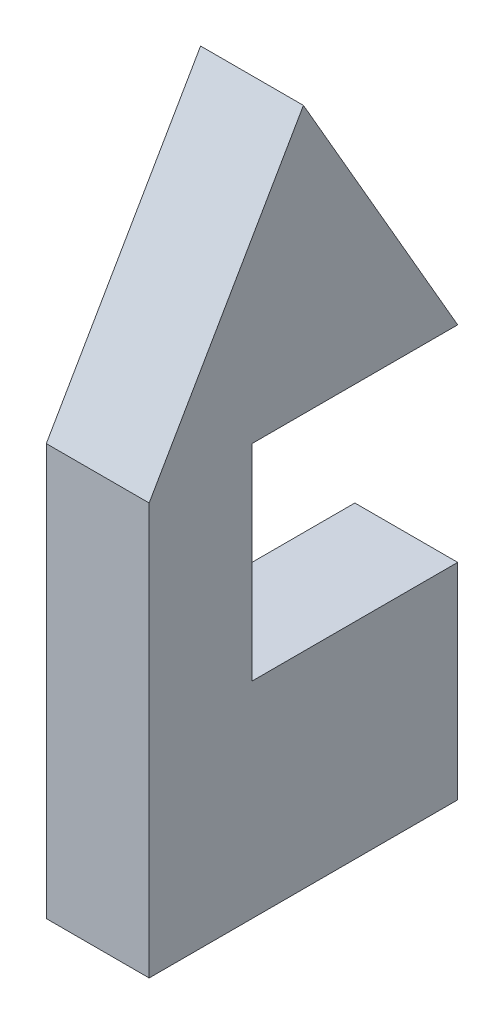
SolidWorks part; units mm, degrees
ref_plane "前视基准面" through (0, 0, 0) normal (0, 0, 1) x (1, 0, 0)
ref_plane "上视基准面" through (0, 0, 0) normal (0, 1, 0) x (1, 0, 0)
ref_plane "右视基准面" through (0, 0, 0) normal (1, 0, 0) x (0, 0, -1)
sketch "草图2" plane through (0, 0, 0) normal (1, 0, 0) x (0, 0, -1)
  line L1 (-2.6044, 1.2724) -> (-0.6044, 1.2724)
  line L2 (-3.6044, 1.2724) -> (-3.6044, -0.7276)
  line L3 (-3.6044, -0.7276) -> (-0.6044, -0.7276)
  line L4 (-0.6044, 1.2724) -> (-0.6044, -0.7276)
  line L8 (-3.6044, 3.2724) -> (-3.6044, 1.2724)
  line L10 (-2.6044, 3.2724) -> (-2.6044, 1.2724)
  line L13 (-0.6044, 3.2724) -> (-2.1044, 5.8705)
  line L14 (-2.1044, 5.8705) -> (-3.6044, 3.2724)
  line L15 (-2.6044, 3.2724) -> (-0.6044, 3.2724)
  point P0 (-2.1044, -0.2276)
  point P5 (-3.1044, 1.2724)
  point P7 (-2.1044, 2.2724)
  point P8 (0, 0)
  point P11 (0, 0)
  point P16 (0, 0)
  dimension "D5" = 2
  dimension "D1" = 3
  dimension "D2" = 2
  dimension "D3" = 1
  dimension "D4" = 2
  dimension "D6" = 3
extrude "凸台-拉伸2" add sketch "草图2" along normal blind 1
